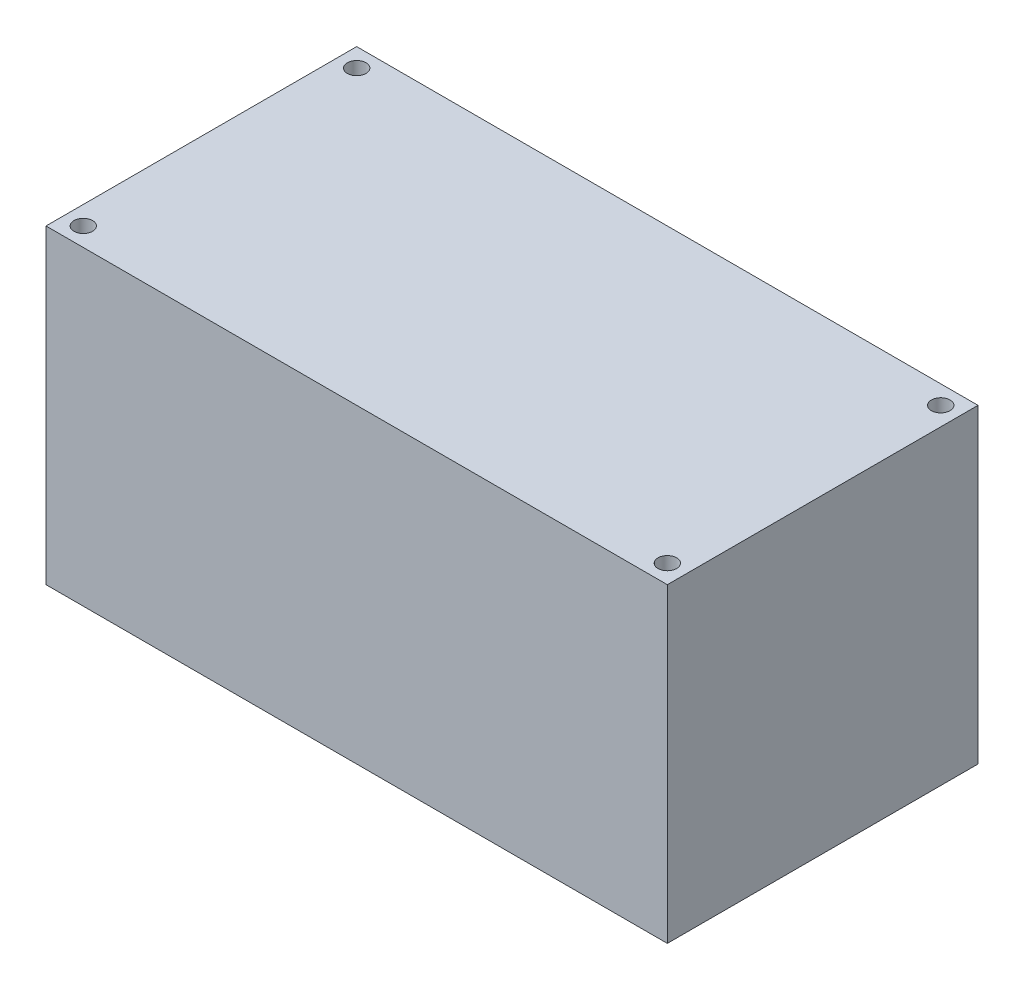
SolidWorks part; units mm, degrees
ref_plane "Plan de face" through (0, 0, 0) normal (0, 0, 1) x (1, 0, 0)
ref_plane "Plan de dessus" through (0, 0, 0) normal (0, 1, 0) x (1, 0, 0)
ref_plane "Plan de droite" through (0, 0, 0) normal (1, 0, 0) x (0, 0, -1)
sketch "Esquisse2" plane through (0, 0, 0) normal (0, 1, 0) x (1, 0, 0)
  line L1 (-50, 25) -> (50, 25)
  line L2 (-50, 25) -> (-50, -25)
  line L3 (-50, -25) -> (50, -25)
  line L4 (50, 25) -> (50, -25)
  dimension "D1" = 100
  dimension "D2" = 50
  dimension "D3" = 50
  dimension "D4" = 25
extrude "Boss.-Extru.1" add sketch "Esquisse2" along normal blind 50
sketch "Esquisse3" plane through (0, 50, 0) normal (0, 1, 0) x (1, 0, 0)
  line L0 (-50, 25) -> (-50, -25) construction
  line L1 (-47, 22) -> (47, 22) construction
  line L2 (-47, 22) -> (-47, -22) construction
  line L3 (-47, -22) -> (47, -22) construction
  line L4 (47, 22) -> (47, -22) construction
  line L5 (50, 25) -> (-50, 25) construction
  line L7 (-50, -25) -> (50, -25) construction
  line L8 (0, 38.0881) -> (0, -39.8087) construction
  circle A0 centre (-47, 22) radius 1.5
  circle A1 centre (-47, -22) radius 1.5
  circle A2 centre (47, -22) radius 1.5
  circle A3 centre (47, 22) radius 1.5
  dimension "D5" = 3
  dimension "D6" = 3
  dimension "D3" = 44
  dimension "D7" = 94
  dimension "D1" = 3
  dimension "D2" = 3
  dimension "D4" = 3
extrude "Enlèv. mat.-Extru.1" cut sketch "Esquisse3" against normal blind 30
equation "\"D3@Esquisse2\"=\"D1@Esquisse2\"/2"
equation "\"D4@Esquisse2\"=\"D2@Esquisse2\"/2"
